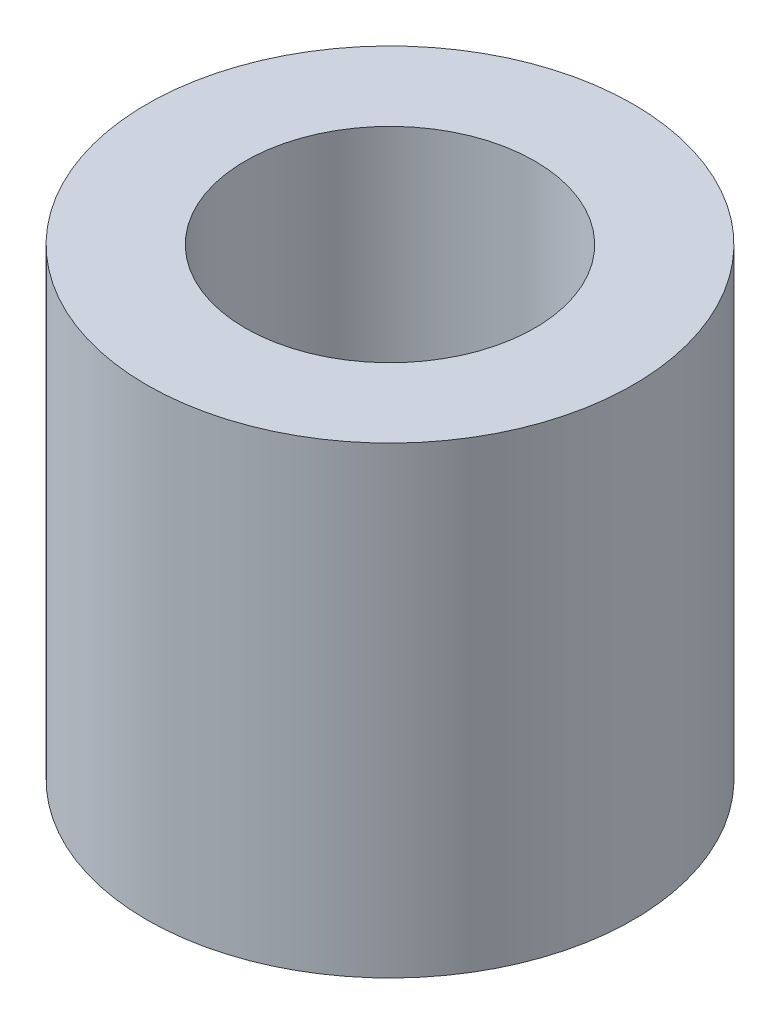
SolidWorks part; units mm, degrees
material "Автоматная латунь, UNS C36000"
ref_plane "Спереди" through (0, 0, 0) normal (0, 0, 1) x (1, 0, 0)
ref_plane "Сверху" through (0, 0, 0) normal (0, 1, 0) x (1, 0, 0)
ref_plane "Справа" through (0, 0, 0) normal (1, 0, 0) x (0, 0, -1)
sketch "Эскиз1" plane through (0, 0, 0) normal (0, 1, 0) x (1, 0, 0)
  circle A0 centre (0, 0) radius 2.1
  dimension "D1" = 4.2
extrude "Бобышка-Вытянуть1" add sketch "Эскиз1" along normal blind 4
hole_wizard "Отверстие обработанное метчиком M31" positions "Эскиз2" profile "Эскиз3" tap size "M3" standard "ISO" end condition through all
sketch "Эскиз2" plane through (0, 4, 0) normal (0, 1, 0) x (1, 0, 0)
  point P0 (0, 0)
sketch "Эскиз3" plane through (0, 4, 0) normal (1, 0, 0) x (0, 0, 1)
  line L0 (0, 0) -> (0, 4)
  line L1 (0, 4) -> (1.25, 4)
  line L2 (1.25, 4) -> (1.25, 0)
  line L5 (1.25, 0) -> (0, 0)
  line L11 (0, -6.35) -> (0, 107.95) construction
  dimension "Диаметр проходного сверла" = 2.5
  dimension "Глубина проходного сверла" = 4
cosmetic thread "Отверстие резьбы1" parameters "D2"=3
